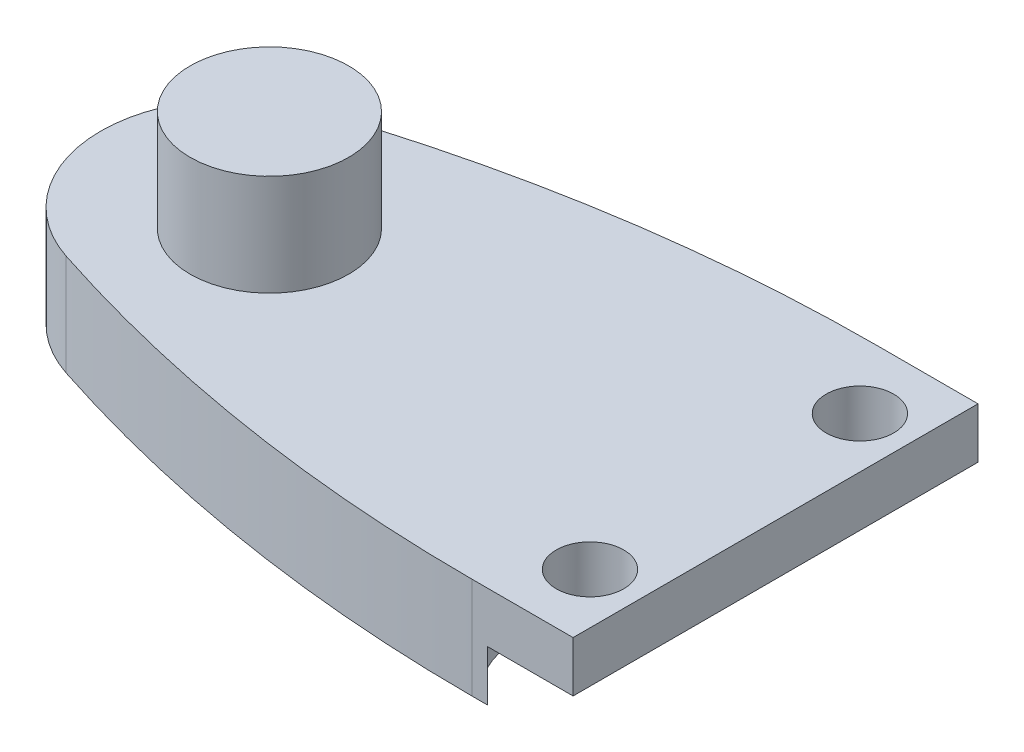
SolidWorks part; units mm, degrees
material "ABS"
ref_plane "Front Plane" through (0, 0, 0) normal (0, 0, 1) x (1, 0, 0)
ref_plane "Top Plane" through (0, 0, 0) normal (0, 1, 0) x (1, 0, 0)
ref_plane "Right Plane" through (0, 0, 0) normal (1, 0, 0) x (0, 0, -1)
sketch "Sketch1" plane through (0, 0, 0) normal (0, 1, 0) x (1, 0, 0)
  line L0 (0, 0) -> (11.2501, 0) construction
  line L1 (-2.3, -3.7228) -> (-2.3, 3.7228) construction
  line L12 (-5, 6) -> (15, 6)
  line L13 (-5, 6) -> (-5, -6)
  line L14 (-5, -6) -> (15, -6)
  line L15 (15, 6) -> (15, -6)
  line L16 (12, -6) -> (15, -6) construction
  line L17 (15, 6) -> (12, 6)
  line L18 (15, 6) -> (15, -6)
  line L19 (15, -6) -> (12, -6)
  line L20 (12, 6) -> (12, -6)
  line L21 (13.5, -6) -> (13.5, 6) construction
  circle A13 centre (0, 0) radius 2.35 construction
  arc A16 (12, -6) -> (-2.3, -3.7228) centre (12, 40.038) cw
  arc A17 (12, 6) -> (-2.3, 3.7228) centre (12, -40.038) ccw
  arc A18 (-2.3, 3.7228) -> (-2.3, -3.7228) centre (-1.0835, 0) ccw
  dimension "D4" = 12
  dimension "D3" = 15.8
  dimension "D2" = 4.7
  dimension "D10" = 20
  dimension "D11" = 5
  dimension "D12" = 3
extrude "Boss-Extrude1" add sketch "Sketch1" against normal blind 3
sketch "Esquisse3" plane through (0, 0, 0) normal (0, 1, 0) x (1, 0, 0)
  circle A0 centre (0, 0) radius 2.35 construction
  circle A1 centre (0, 0) radius 2.35
extrude "Boss.-Extru.2" add sketch "Esquisse3" along normal blind 3
sketch "Esquisse4" plane through (0, 0, 0) normal (0, 1, 0) x (1, 0, 0)
  line L0 (13.5, -6) -> (13.5, 6) construction
  line L1 (12, -6) -> (15, -6) construction
  line L2 (12, 6) -> (15, 6) construction
  line L3 (15, 0) -> (11.0196, 0) construction
  line L4 (15, 6) -> (15, -6) construction
  circle A0 centre (13.5, -4) radius 1
  circle A1 centre (13.5, 4) radius 1
  dimension "D2" = 2
  dimension "D3" = 2
  dimension "D1" = 8
extrude "Enlèv. mat.-Extru.1" cut sketch "Esquisse4" against normal blind 10
sketch "Esquisse5" plane through (0, -3, 0) normal (0, -1, 0) x (1, 0, 0)
  line L0 (13.5, 6.25) -> (13.5, 10.0378)
  line L1 (13.5, 10.0378) -> (19.161, 10.0378)
  line L2 (19.161, 10.0378) -> (18.7112, -10.097)
  line L3 (18.7112, -10.097) -> (13.5, -10.097)
  line L4 (13.5, -10.097) -> (13.5, -6.25)
  line L5 (13.5, 1.75) -> (13.5, -1.75)
  arc A0 (13.5, 6.25) -> (13.5, 1.75) centre (13.5, 4) ccw
  arc A1 (13.5, -1.75) -> (13.5, -6.25) centre (13.5, -4) ccw
  circle A2 centre (13.5, 4) radius 1 construction
  circle A3 centre (13.5, -4) radius 1 construction
  dimension "D1" = 4.5
  dimension "D2" = 4.5
extrude "Enlèv. mat.-Extru.2" cut sketch "Esquisse5" against normal blind 1.5
